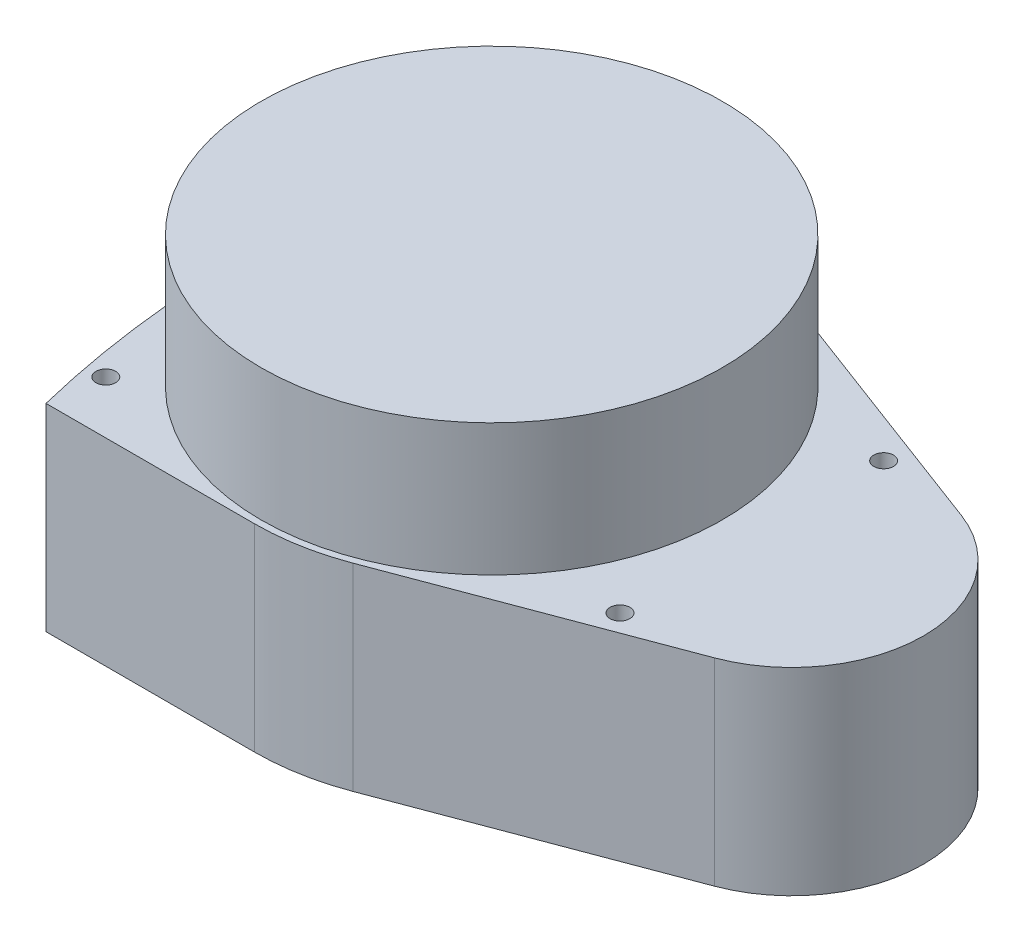
SolidWorks part; units mm, degrees
ref_plane "前视基准面" through (0, 0, 0) normal (0, 0, 1) x (1, 0, 0)
ref_plane "上视基准面" through (0, 0, 0) normal (0, 1, 0) x (1, 0, 0)
ref_plane "右视基准面" through (0, 0, 0) normal (1, 0, 0) x (0, 0, -1)
sketch "草图1" plane through (0, 0, 0) normal (0, 1, 0) x (1, 0, 0)
  circle A0 centre (0, 0) radius 35
  dimension "D1" = 70
extrude "凸台-拉伸1" add sketch "草图1" along normal blind 20
sketch "草图2" plane through (0, 0, 0) normal (0, 1, 0) x (1, 0, 0)
  line L0 (-57.0081, 0) -> (83.969, 0) construction
  line L1 (52.533, 18.7226) -> (12.6593, 33.7008)
  line L3 (-35, 0) -> (-35, 28) construction
  line L4 (0, 36) -> (-31.6159, 36)
  line L6 (-36, 0) -> (65.5, 0)
  circle A0 centre (45.5, 0) radius 7.5 construction
  arc A3 (-31.6159, 36) -> (-36, 0) centre (114, 0) ccw
  arc A4 (12.6593, 33.7008) -> (0, 36) centre (0, 0) ccw
  arc A5 (65.5, 0) -> (52.533, 18.7226) centre (45.5, 0) ccw
  dimension "D1" = 15
  dimension "D3" = 20
  dimension "D4" = 300
  dimension "D6" = 36
  dimension "D2" = 45.5
  dimension "D5" = 28
extrude "凸台-拉伸2" add sketch "草图2" against normal blind 30
mirror "镜向1" about plane through (-36, -30, 0) normal (0, 0, 1) of "凸台-拉伸2"
sketch "草图4" plane through (0, 0, 0) normal (0, 1, 0) x (1, 0, 0)
  line L0 (-47.2387, 0) -> (70.6055, 0) construction
  circle A0 centre (-30.54, 28) radius 1.5
  circle A1 centre (39.46, 20) radius 1.5
  dimension "D1" = 3
  dimension "D2" = 3
  dimension "D5" = 30.54
  dimension "D3" = 20
  dimension "D4" = 28
  dimension "D6" = 39.46
extrude "切除-拉伸1" cut sketch "草图4" against normal through all
mirror "镜向2" about plane through (0, 0, 0) normal (0, 0, 1) of "切除-拉伸1"
